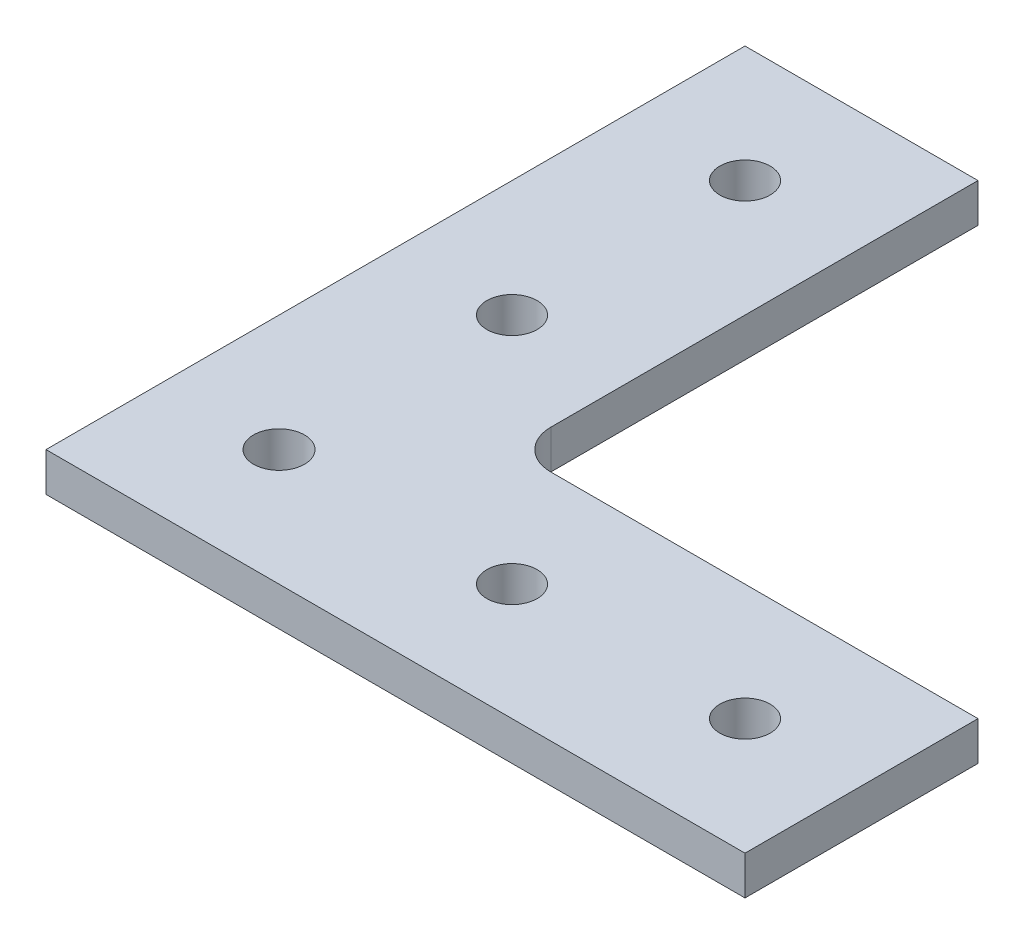
SolidWorks part; units mm, degrees
ref_plane "Front Plane" through (0, 0, 0) normal (0, 0, 1) x (1, 0, 0)
ref_plane "Top Plane" through (0, 0, 0) normal (0, 1, 0) x (1, 0, 0)
ref_plane "Right Plane" through (0, 0, 0) normal (1, 0, 0) x (0, 0, -1)
sketch "Sketch1" plane through (0, 0, 0) normal (0, 1, 0) x (1, 0, 0)
  line L0 (-94.4217, 44.6078) -> (-94.4217, -69.6922)
  line L1 (-94.4217, -69.6922) -> (19.8783, -69.6922)
  line L2 (19.8783, -69.6922) -> (19.8783, -31.5922)
  line L3 (19.8783, -31.5922) -> (-49.9717, -31.5922)
  line L4 (-56.3217, -25.2422) -> (-56.3217, 44.6078)
  line L5 (-56.3217, 44.6078) -> (-94.4217, 44.6078)
  arc A0 (-56.3217, -25.2422) -> (-49.9717, -31.5922) centre (-49.9717, -25.2422) ccw
  circle A1 centre (-75.3717, -50.6422) radius 4.1656
  circle A2 centre (0.8283, -50.6422) radius 4.1148
  circle A3 centre (-37.2717, -50.6422) radius 4.1148
  circle A4 centre (-75.3717, 25.5578) radius 4.1148
  circle A5 centre (-75.3717, -12.5422) radius 4.1148
  dimension "D5" = 6.35
  dimension "D6" = 19.05
  dimension "D8" = 19.05
  dimension "D12" = 19.05
  dimension "D14" = 19.05
  dimension "D1" = 114.3
  dimension "D2" = 114.3
  dimension "D3" = 38.1
  dimension "D4" = 38.1
  dimension "D7" = 19.05
  dimension "D9" = 38.1
  dimension "D10" = 19.05
  dimension "D11" = 19.05
  dimension "D13" = 19.05
  dimension "D15" = 38.1
extrude "Boss-Extrude1" add sketch "Sketch1" along normal blind 6.35
